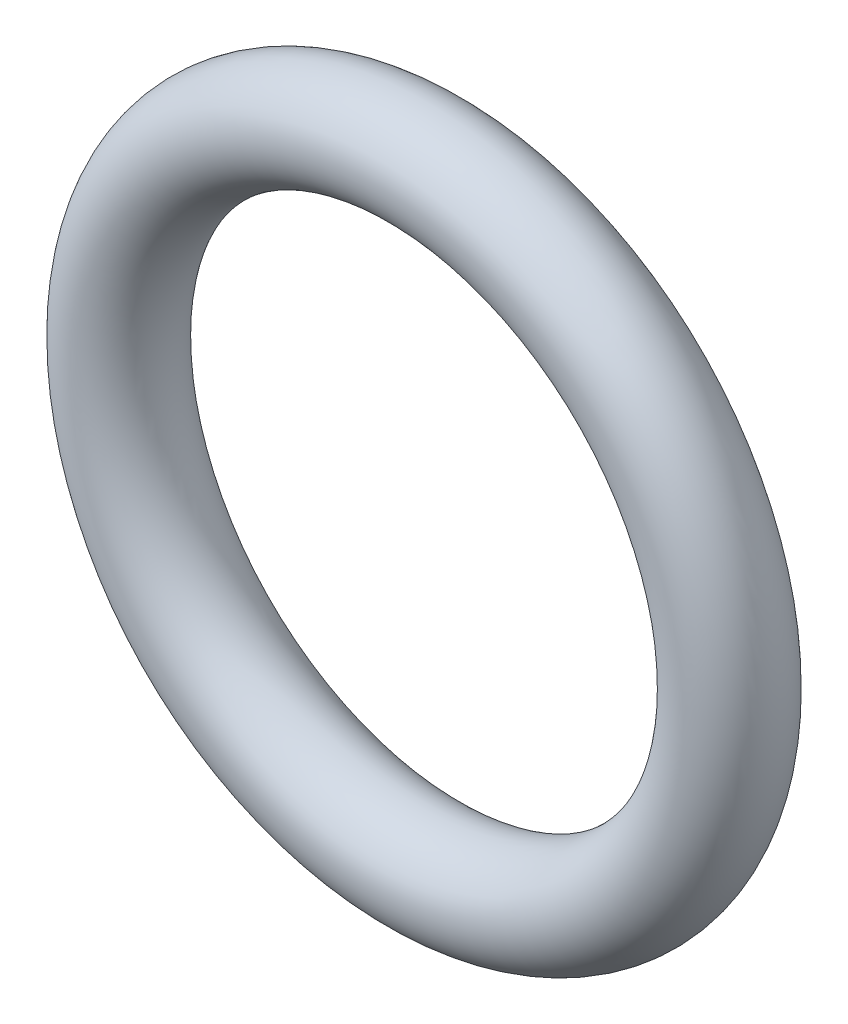
SolidWorks part; units mm, degrees
ref_plane "Front Plane" through (0, 0, 0) normal (0, 0, 1) x (1, 0, 0)
ref_plane "Top Plane" through (0, 0, 0) normal (0, 1, 0) x (1, 0, 0)
ref_plane "Right Plane" through (0, 0, 0) normal (1, 0, 0) x (0, 0, -1)
sketch "Sketch1" plane through (0, 0, 0) normal (0, 1, 0) x (1, 0, 0)
  line L0 (0, 0) -> (152.4, 0) construction
  line L1 (152.4, 0) -> (152.4, 70.2398) construction
  circle A0 centre (0, 0) radius 25.4
revolve "Revolve1" add sketch "Sketch1" angle 360 about L1
